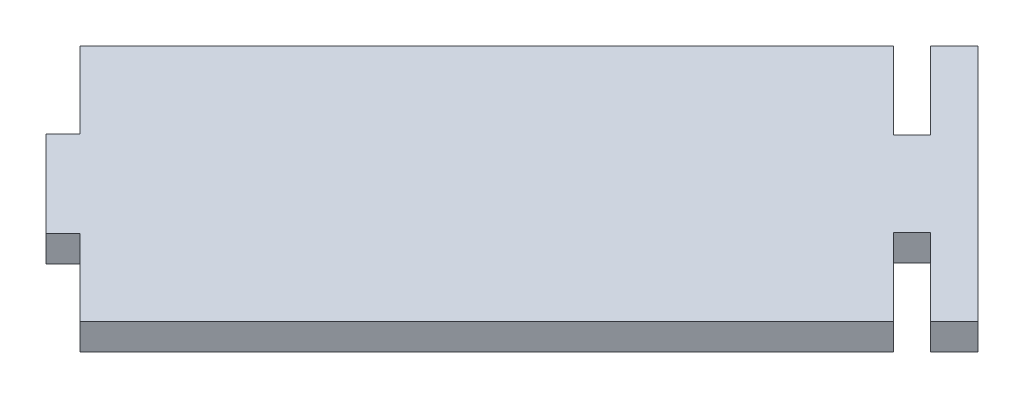
SolidWorks part; units mm, degrees
material "cardboard"
ref_plane "Front Plane" through (0, 0, 0) normal (0, 0, 1) x (1, 0, 0)
ref_plane "Top Plane" through (0, 0, 0) normal (0, 1, 0) x (1, 0, 0)
ref_plane "Right Plane" through (0, 0, 0) normal (1, 0, 0) x (0, 0, -1)
sketch "Sketch1" plane through (0, 0, 0) normal (0, 1, 0) x (1, 0, 0)
  line L0 (-130.0272, 126.0966) -> (-119.0272, 126.0966)
  line L1 (-120.0272, 122.0966) -> (-120.0272, 106.0966)
  line L2 (-60.2272, 122.0966) -> (-60.2272, 106.0966)
  line L3 (-117.6272, 106.0966) -> (-120.0272, 106.0966)
  line L4 (-131.4272, 122.0966) -> (-129.0272, 122.0966)
  line L5 (-131.4272, 122.0966) -> (-131.4272, 106.0966)
  line L6 (-131.4272, 106.0966) -> (-129.0272, 106.0966)
  line L7 (-129.0272, 122.0966) -> (-129.0272, 106.0966)
  line L8 (-117.6272, 122.0966) -> (-117.6272, 106.0966)
  line L9 (-117.6272, 122.0966) -> (-120.0272, 122.0966)
  line L10 (-57.8272, 122.0966) -> (-57.8272, 106.0966)
  line L11 (-94.4272, 126.0966) -> (-83.4272, 126.0966)
  line L12 (-60.2272, 122.0966) -> (-57.8272, 122.0966)
  line L13 (-60.2272, 106.0966) -> (-57.8272, 106.0966)
  line L14 (-48.8272, 122.0966) -> (-48.8272, 106.0966)
  line L15 (-46.4272, 122.0966) -> (-48.8272, 122.0966)
  line L16 (-46.4272, 122.0966) -> (-46.4272, 106.0966)
  line L17 (-46.4272, 106.0966) -> (-48.8272, 106.0966)
  line L18 (10.9728, 122.0966) -> (10.9728, 106.0966)
  line L19 (13.3728, 122.0966) -> (13.3728, 106.0966)
  line L20 (10.9728, 122.0966) -> (13.3728, 122.0966)
  line L21 (10.9728, 106.0966) -> (13.3728, 106.0966)
  line L22 (22.3728, 122.0966) -> (22.3728, 106.0966)
  line L23 (24.7728, 122.0966) -> (22.3728, 122.0966)
  line L24 (24.7728, 122.0966) -> (24.7728, 106.0966)
  line L25 (24.7728, 106.0966) -> (22.3728, 106.0966)
  line L26 (82.1728, 122.0966) -> (82.1728, 106.0966)
  line L27 (84.5728, 122.0966) -> (84.5728, 106.0966)
  line L28 (-58.8272, 126.0966) -> (-47.8272, 126.0966)
  line L29 (82.1728, 122.0966) -> (84.5728, 122.0966)
  line L30 (82.1728, 106.0966) -> (84.5728, 106.0966)
  line L31 (93.5728, 122.0966) -> (93.5728, 106.0966)
  line L32 (58.9728, 128.0966) -> (83.5728, 128.0966)
  line L33 (95.9728, 122.0966) -> (93.5728, 122.0966)
  line L34 (95.9728, 122.0966) -> (95.9728, 106.0966)
  line L35 (95.9728, 106.0966) -> (93.5728, 106.0966)
  line L36 (65.0298, 36.0601) -> (71.4457, 29.6442)
  line L37 (84.9326, 16.1573) -> (86.9125, 18.1372)
  line L38 (65.0298, 36.0601) -> (67.0097, 38.04)
  line L39 (78.5168, 22.5731) -> (84.9326, 16.1573)
  line L40 (84.9326, -86.6937) -> (78.5168, -93.1095)
  line L41 (84.9326, -86.6937) -> (86.9125, -88.6736)
  line L42 (86.9125, -88.6736) -> (67.0097, -108.5764)
  line L43 (65.0298, -106.5965) -> (67.0097, -108.5764)
  line L44 (71.4457, -100.1806) -> (65.0298, -106.5965)
  line L45 (-37.8211, -106.5965) -> (-44.237, -100.1806)
  line L46 (-37.8211, -106.5965) -> (-39.801, -108.5764)
  line L47 (-39.801, -108.5764) -> (-59.7038, -88.6736)
  line L48 (-57.7239, -86.6937) -> (-59.7038, -88.6736)
  line L49 (-51.308, -93.1095) -> (-57.7239, -86.6937)
  line L50 (-23.2272, 126.0966) -> (-12.2272, 126.0966)
  line L51 (12.3728, 126.0966) -> (23.3728, 126.0966)
  line L52 (47.9728, 126.0966) -> (58.9728, 126.0966)
  line L53 (83.5728, 126.0966) -> (94.5728, 126.0966)
  line L54 (119.1728, 126.0966) -> (130.1728, 126.0966)
  line L55 (-34.4977, -103.2731) -> (-32.4283, -105.3425)
  line L56 (-4.0921, -77.1101) -> (-2.0227, -79.1795)
  line L57 (-54.4005, -83.3703) -> (-56.1683, -85.138)
  line L58 (-34.4977, -103.2731) -> (-36.2655, -105.0408)
  line L59 (-30.307, -50.8953) -> (-56.4699, -77.0582)
  line L60 (-56.4699, -81.3008) -> (-54.4005, -83.3703)
  line L61 (-2.0227, -79.1795) -> (-28.1856, -105.3425)
  line L62 (-30.307, -50.8953) -> (-28.2375, -52.9647)
  line L63 (-142.3272, 128.0966) -> (-130.0272, 128.0966)
  line L64 (-53.7115, 80.7984) -> (-53.7115, 85.7984)
  line L65 (-63.7115, 80.7984) -> (-63.7115, 85.7984)
  line L66 (-33.1616, 72.2863) -> (-29.6261, 75.8218)
  line L67 (-26.0906, 65.2152) -> (-22.555, 68.7508)
  line L68 (-17.5785, 44.6653) -> (-12.5785, 44.6653)
  line L69 (-17.5785, 34.6653) -> (-12.5785, 34.6653)
  line L70 (-26.0906, 14.1154) -> (-22.555, 10.5799)
  line L71 (-33.1616, 7.0443) -> (-29.6261, 3.5088)
  line L72 (-53.7115, -1.4677) -> (-53.7115, -6.4677)
  line L73 (-63.7115, -1.4677) -> (-63.7115, -6.4677)
  line L74 (-84.2615, 7.0443) -> (-87.797, 3.5088)
  line L75 (63.4742, 34.5044) -> (69.8901, 28.0886)
  line L76 (76.9611, 21.0175) -> (83.377, 14.6016)
  line L77 (76.9611, 21.0175) -> (78.5168, 22.5731)
  line L78 (69.8901, 28.0886) -> (71.4457, 29.6442)
  line L79 (31.6778, -78.9012) -> (34.5062, -76.0728)
  line L80 (57.2374, -17.1948) -> (54.409, -14.3664)
  line L81 (-142.3272, 128.0966) -> (-142.3272, 118.0966)
  line L82 (-4.469, 8.3648) -> (-30.0287, -17.1948)
  line L83 (-142.3272, 100.0966) -> (-126.5272, 100.0966)
  line L84 (-91.3325, 14.1154) -> (-94.8681, 10.5799)
  line L85 (-106.7272, 119.0966) -> (-106.7272, 109.0966)
  line L86 (67.0097, 38.04) -> (86.9125, 18.1372)
  line L87 (-20.8129, -49.7827) -> (-0.9101, -69.6855)
  line L88 (-20.8129, -49.7827) -> (-23.9949, -52.9647)
  line L89 (-0.9101, -69.6855) -> (-4.0921, -72.8675)
  line L90 (-30.0287, -17.1948) -> (-65.0287, -17.1948)
  line L91 (-80.0287, -32.1948) -> (-80.0287, -38.3416)
  line L92 (-65.0287, -53.3416) -> (-32.7533, -53.3416)
  line L93 (-110.0272, 105.0966) -> (-112.5272, 105.0966)
  line L94 (-139.0272, 125.0966) -> (-136.5272, 125.0966)
  line L95 (-139.0272, 125.0966) -> (-139.0272, 105.0966)
  line L96 (-139.0272, 105.0966) -> (-136.5272, 105.0966)
  line L97 (-136.5272, 125.0966) -> (-136.5272, 105.0966)
  line L98 (-112.5272, 125.0966) -> (-112.5272, 105.0966)
  line L99 (31.6778, 8.3648) -> (31.6778, 43.3648)
  line L100 (16.6778, 58.3648) -> (10.531, 58.3648)
  line L101 (-4.469, 43.3648) -> (-4.469, 8.3648)
  line L102 (-110.0272, 125.0966) -> (-112.5272, 125.0966)
  line L103 (-110.0272, 125.0966) -> (-110.0272, 105.0966)
  line L104 (-122.5272, 100.0966) -> (-108.2272, 100.0966)
  line L105 (-106.7272, 119.0966) -> (-106.7272, 109.0966)
  line L106 (57.2374, -53.3416) -> (92.2374, -53.3416)
  line L107 (107.2374, -38.3416) -> (107.2374, -32.1948)
  line L108 (92.2374, -17.1948) -> (57.2374, -17.1948)
  line L109 (-72.6272, 100.0966) -> (-71.1272, 100.0966)
  line L110 (-71.1272, 128.0966) -> (-71.1272, 100.0966)
  line L111 (23.3728, 128.0966) -> (47.9728, 128.0966)
  line L112 (-71.1272, 128.0966) -> (-71.1272, 100.0966)
  line L113 (-71.1272, 100.0966) -> (-35.5272, 100.0966)
  line L114 (-35.5272, 128.0966) -> (-35.5272, 100.0966)
  line L115 (-4.469, -81.6259) -> (-4.469, -113.9012)
  line L116 (10.531, -128.9012) -> (16.6778, -128.9012)
  line L117 (31.6778, -113.9012) -> (31.6778, -78.9012)
  line L118 (-12.2272, 128.0966) -> (12.3728, 128.0966)
  line L119 (-35.5272, 128.0966) -> (-35.5272, 100.0966)
  line L120 (-35.5272, 100.0966) -> (0.0728, 100.0966)
  line L121 (0.0728, 128.0966) -> (0.0728, 100.0966)
  line L122 (-47.8272, 128.0966) -> (-23.2272, 128.0966)
  line L123 (0.0728, 128.0966) -> (0.0728, 100.0966)
  line L124 (54.409, -56.17) -> (57.2374, -53.3416)
  line L125 (28.1189, -69.6855) -> (48.0217, -49.7827)
  line L126 (83.377, -85.138) -> (76.9611, -91.5539)
  line L127 (48.0217, -49.7827) -> (83.377, -85.138)
  line L128 (76.9611, -91.5539) -> (78.5168, -93.1095)
  line L129 (80.4967, -95.0894) -> (73.4256, -102.1605)
  line L130 (28.1189, -69.6855) -> (63.4742, -105.0408)
  line L131 (69.8901, -98.625) -> (71.4457, -100.1806)
  line L132 (69.8901, -98.625) -> (63.4742, -105.0408)
  line L133 (-36.2655, -105.0408) -> (-42.6813, -98.625)
  line L134 (-42.6813, -98.625) -> (-44.237, -100.1806)
  line L135 (34.5062, 5.5364) -> (31.6778, 8.3648)
  line L136 (-99.8446, 34.6653) -> (-104.8446, 34.6653)
  line L137 (48.0217, -20.7537) -> (28.1189, -0.8509)
  line L138 (48.0217, -20.7537) -> (83.377, 14.6016)
  line L139 (28.1189, -0.8509) -> (63.4742, 34.5044)
  line L140 (-46.2169, -102.1605) -> (-53.2879, -95.0894)
  line L141 (-49.7524, -91.5539) -> (-51.308, -93.1095)
  line L142 (-49.7524, -91.5539) -> (-56.1683, -85.138)
  line L143 (-63.7115, 80.7984) -> (-75.7494, 80.7984)
  line L144 (-75.7494, 80.7984) -> (-84.2615, 72.2863)
  line L145 (0.0728, 100.0966) -> (35.6728, 100.0966)
  line L146 (35.6728, 128.0966) -> (35.6728, 100.0966)
  line L147 (-83.4272, 128.0966) -> (-58.8272, 128.0966)
  line L148 (35.6728, 128.0966) -> (35.6728, 100.0966)
  line L149 (35.6728, 100.0966) -> (71.2728, 100.0966)
  line L150 (71.2728, 128.0966) -> (71.2728, 100.0966)
  line L151 (-119.0272, 128.0966) -> (-108.2272, 128.0966)
  line L152 (71.2728, 128.0966) -> (71.2728, 100.0966)
  line L153 (71.2728, 100.0966) -> (106.8728, 100.0966)
  line L154 (106.8728, 128.0966) -> (106.8728, 100.0966)
  line L155 (130.1728, 128.0966) -> (142.4728, 128.0966)
  line L156 (106.8728, 128.0966) -> (106.8728, 100.0966)
  line L157 (106.8728, 100.0966) -> (142.4728, 100.0966)
  line L158 (142.4728, 128.0966) -> (142.4728, 118.0966)
  line L159 (-67.8272, 125.0966) -> (-65.3272, 125.0966)
  line L160 (-67.8272, 125.0966) -> (-67.8272, 105.0966)
  line L161 (-67.8272, 105.0966) -> (-65.3272, 105.0966)
  line L162 (-65.3272, 125.0966) -> (-65.3272, 105.0966)
  line L163 (-41.3272, 125.0966) -> (-41.3272, 105.0966)
  line L164 (-38.8272, 105.0966) -> (-41.3272, 105.0966)
  line L165 (-38.8272, 125.0966) -> (-38.8272, 105.0966)
  line L166 (-38.8272, 125.0966) -> (-41.3272, 125.0966)
  line L167 (-59.3272, 100.0966) -> (-59.3272, 96.0966)
  line L168 (-59.3272, 96.0966) -> (-47.3272, 96.0966)
  line L169 (-47.3272, 96.0966) -> (-47.3272, 100.0966)
  line L170 (3.3728, 125.0966) -> (5.8728, 125.0966)
  line L171 (3.3728, 125.0966) -> (3.3728, 105.0966)
  line L172 (3.3728, 105.0966) -> (5.8728, 105.0966)
  line L173 (5.8728, 125.0966) -> (5.8728, 105.0966)
  line L174 (29.8728, 125.0966) -> (29.8728, 105.0966)
  line L175 (32.3728, 105.0966) -> (29.8728, 105.0966)
  line L176 (32.3728, 125.0966) -> (32.3728, 105.0966)
  line L177 (32.3728, 125.0966) -> (29.8728, 125.0966)
  line L178 (11.8728, 100.0966) -> (11.8728, 96.0966)
  line L179 (11.8728, 96.0966) -> (23.8728, 96.0966)
  line L180 (23.8728, 96.0966) -> (23.8728, 100.0966)
  line L181 (74.5728, 125.0966) -> (77.0728, 125.0966)
  line L182 (74.5728, 125.0966) -> (74.5728, 105.0966)
  line L183 (74.5728, 105.0966) -> (77.0728, 105.0966)
  line L184 (77.0728, 125.0966) -> (77.0728, 105.0966)
  line L185 (101.0728, 125.0966) -> (101.0728, 105.0966)
  line L186 (103.5728, 105.0966) -> (101.0728, 105.0966)
  line L187 (103.5728, 125.0966) -> (103.5728, 105.0966)
  line L188 (103.5728, 125.0966) -> (101.0728, 125.0966)
  line L189 (83.0728, 100.0966) -> (83.0728, 96.0966)
  line L190 (83.0728, 96.0966) -> (95.0728, 96.0966)
  line L191 (95.0728, 96.0966) -> (95.0728, 100.0966)
  line L192 (-126.5272, 100.0966) -> (-126.5272, 101.0966)
  line L193 (-126.5272, 101.0966) -> (-122.5272, 101.0966)
  line L194 (-122.5272, 101.0966) -> (-122.5272, 100.0966)
  line L195 (-59.3272, 99.0966) -> (-55.3272, 99.0966)
  line L196 (-55.3272, 99.0966) -> (-55.3272, 101.0966)
  line L197 (-55.3272, 101.0966) -> (-51.3272, 101.0966)
  line L198 (-51.3272, 101.0966) -> (-51.3272, 99.0966)
  line L199 (-51.3272, 99.0966) -> (-47.3272, 99.0966)
  line L200 (11.8728, 99.0966) -> (15.8728, 99.0966)
  line L201 (15.8728, 99.0966) -> (15.8728, 101.0966)
  line L202 (15.8728, 101.0966) -> (19.8728, 101.0966)
  line L203 (29.5331, 0.5633) -> (35.897, -5.8007)
  line L204 (35.897, -5.8007) -> (33.0686, -8.6291)
  line L205 (33.0686, -8.6291) -> (40.2435, -15.8039)
  line L206 (40.2435, -15.8039) -> (43.0719, -12.9755)
  line L207 (43.0719, -12.9755) -> (49.4359, -19.3395)
  line L208 (49.4359, -51.1969) -> (43.0719, -57.5609)
  line L209 (43.0719, -57.5609) -> (40.2435, -54.7324)
  line L210 (40.2435, -54.7324) -> (33.0686, -61.9073)
  line L211 (33.0686, -61.9073) -> (35.897, -64.7357)
  line L212 (35.897, -64.7357) -> (29.5331, -71.0997)
  line L213 (-2.3243, -71.0997) -> (-8.6883, -64.7357)
  line L214 (-8.6883, -64.7357) -> (-5.8599, -61.9073)
  line L215 (-5.8599, -61.9073) -> (-13.0347, -54.7324)
  line L216 (-13.0347, -54.7324) -> (-15.8632, -57.5609)
  line L217 (-15.8632, -57.5609) -> (-22.2271, -51.1969)
  line L218 (-87.797, 75.8218) -> (-94.8681, 68.7508)
  line L219 (-91.3325, 65.2152) -> (-99.8446, 56.7032)
  line L220 (-99.8446, 56.7032) -> (-99.8446, 44.6653)
  line L221 (-104.8446, 44.6653) -> (-104.8446, 34.6653)
  line L222 (-99.8446, 34.6653) -> (-99.8446, 22.6275)
  line L223 (-99.8446, 22.6275) -> (-91.3325, 14.1154)
  line L224 (-94.8681, 10.5799) -> (-87.797, 3.5088)
  line L225 (-84.2615, 7.0443) -> (-75.7494, -1.4677)
  line L226 (-75.7494, -1.4677) -> (-63.7115, -1.4677)
  line L227 (-63.7115, -6.4677) -> (-53.7115, -6.4677)
  line L228 (-53.7115, -1.4677) -> (-41.6737, -1.4677)
  line L229 (-41.6737, -1.4677) -> (-33.1616, 7.0443)
  line L230 (-29.6261, 3.5088) -> (-22.555, 10.5799)
  line L231 (-26.0906, 14.1154) -> (-17.5785, 22.6275)
  line L232 (-17.5785, 22.6275) -> (-17.5785, 34.6653)
  line L233 (-12.5785, 34.6653) -> (-12.5785, 44.6653)
  line L234 (-17.5785, 44.6653) -> (-17.5785, 56.7032)
  line L235 (-17.5785, 56.7032) -> (-26.0906, 65.2152)
  line L236 (-22.555, 68.7508) -> (-29.6261, 75.8218)
  line L237 (-33.1616, 72.2863) -> (-41.6737, 80.7984)
  line L238 (-41.6737, 80.7984) -> (-53.7115, 80.7984)
  line L239 (-53.7115, 85.7984) -> (-63.7115, 85.7984)
  line L240 (-99.8446, 44.6653) -> (-104.8446, 44.6653)
  line L241 (-91.3325, 65.2152) -> (-94.8681, 68.7508)
  line L242 (-84.2615, 72.2863) -> (-87.797, 75.8218)
  line L243 (19.8728, 101.0966) -> (19.8728, 99.0966)
  line L244 (19.8728, 99.0966) -> (23.8728, 99.0966)
  line L245 (83.0728, 99.0966) -> (87.0728, 99.0966)
  line L246 (87.0728, 99.0966) -> (87.0728, 101.0966)
  line L247 (87.0728, 101.0966) -> (91.0728, 101.0966)
  line L248 (91.0728, 101.0966) -> (91.0728, 99.0966)
  line L249 (91.0728, 99.0966) -> (95.0728, 99.0966)
  line L250 (142.4728, 118.0966) -> (144.4728, 118.0966)
  line L251 (144.4728, 110.0966) -> (142.4728, 110.0966)
  line L252 (142.4728, 110.0966) -> (142.4728, 100.0966)
  line L253 (-142.3272, 118.0966) -> (-141.3272, 118.0966)
  line L254 (-141.3272, 118.0966) -> (-141.3272, 110.0966)
  line L255 (-141.3272, 110.0966) -> (-142.3272, 110.0966)
  line L256 (-142.3272, 110.0966) -> (-142.3272, 100.0966)
  line L257 (-108.2272, 128.0966) -> (-108.2272, 119.0966)
  line L258 (-108.2272, 119.0966) -> (-106.7272, 119.0966)
  line L259 (-106.7272, 109.0966) -> (-108.2272, 109.0966)
  line L260 (-108.2272, 109.0966) -> (-108.2272, 100.0966)
  line L261 (-72.6272, 128.0966) -> (-72.6272, 119.0966)
  line L262 (-72.6272, 119.0966) -> (-69.6272, 119.0966)
  line L263 (-69.6272, 119.0966) -> (-69.6272, 109.0966)
  line L264 (-69.6272, 109.0966) -> (-72.6272, 109.0966)
  line L265 (-72.6272, 109.0966) -> (-72.6272, 100.0966)
  line L266 (-37.0272, 128.0966) -> (-37.0272, 119.0966)
  line L267 (-37.0272, 119.0966) -> (-34.0272, 119.0966)
  line L268 (-34.0272, 119.0966) -> (-34.0272, 109.0966)
  line L269 (-34.0272, 109.0966) -> (-37.0272, 109.0966)
  line L270 (-37.0272, 109.0966) -> (-37.0272, 100.0966)
  line L271 (-1.4272, 128.0966) -> (-1.4272, 119.0966)
  line L272 (-1.4272, 119.0966) -> (1.5728, 119.0966)
  line L273 (1.5728, 119.0966) -> (1.5728, 109.0966)
  line L274 (1.5728, 109.0966) -> (-1.4272, 109.0966)
  line L275 (-1.4272, 109.0966) -> (-1.4272, 100.0966)
  line L276 (34.1728, 128.0966) -> (34.1728, 119.0966)
  line L277 (34.1728, 119.0966) -> (37.1728, 119.0966)
  line L278 (37.1728, 119.0966) -> (37.1728, 109.0966)
  line L279 (37.1728, 109.0966) -> (34.1728, 109.0966)
  line L280 (34.1728, 109.0966) -> (34.1728, 100.0966)
  line L281 (69.7728, 128.0966) -> (69.7728, 119.0966)
  line L282 (69.7728, 119.0966) -> (72.7728, 119.0966)
  line L283 (72.7728, 119.0966) -> (72.7728, 109.0966)
  line L284 (72.7728, 109.0966) -> (69.7728, 109.0966)
  line L285 (69.7728, 109.0966) -> (69.7728, 100.0966)
  line L286 (105.3728, 128.0966) -> (105.3728, 119.0966)
  line L287 (105.3728, 119.0966) -> (108.3728, 119.0966)
  line L288 (108.3728, 119.0966) -> (108.3728, 109.0966)
  line L289 (108.3728, 109.0966) -> (105.3728, 109.0966)
  line L290 (105.3728, 109.0966) -> (105.3728, 100.0966)
  line L291 (144.4728, 118.0966) -> (144.4728, 110.0966)
  line L292 (-130.0272, 128.0966) -> (-130.0272, 126.0966)
  line L293 (-119.0272, 128.0966) -> (-119.0272, 126.0966)
  line L294 (-94.4272, 128.0966) -> (-94.4272, 126.0966)
  line L295 (-83.4272, 128.0966) -> (-83.4272, 126.0966)
  line L296 (-58.8272, 128.0966) -> (-58.8272, 126.0966)
  line L297 (-47.8272, 128.0966) -> (-47.8272, 126.0966)
  line L298 (-23.2272, 128.0966) -> (-23.2272, 126.0966)
  line L299 (-12.2272, 128.0966) -> (-12.2272, 126.0966)
  line L300 (12.3728, 128.0966) -> (12.3728, 126.0966)
  line L301 (23.3728, 128.0966) -> (23.3728, 126.0966)
  line L302 (47.9728, 128.0966) -> (47.9728, 126.0966)
  line L303 (58.9728, 128.0966) -> (58.9728, 126.0966)
  line L304 (83.5728, 128.0966) -> (83.5728, 126.0966)
  line L305 (94.5728, 128.0966) -> (94.5728, 126.0966)
  line L306 (119.1728, 128.0966) -> (119.1728, 126.0966)
  line L307 (130.1728, 128.0966) -> (130.1728, 126.0966)
  line L308 (94.5728, 128.0966) -> (119.1728, 128.0966)
  circle A0 centre (-30.307, -57.9663) radius 1.75
  circle A1 centre (-58.7115, 66.6653) radius 6
  circle A2 centre (-39.6197, 58.7572) radius 6
  circle A3 centre (-31.7115, 39.6653) radius 6
  circle A4 centre (-9.0938, -79.1795) radius 1.75
  circle A5 centre (-30.307, -100.3927) radius 1.75
  circle A6 centre (13.6044, 33.3648) radius 10
  circle A7 centre (-124.5272, 112.5966) radius 1
  circle A8 centre (-51.5202, -79.1795) radius 1.75
  arc A9 (-28.2375, -52.9647) -> (-23.9949, -52.9647) centre (-26.1162, -50.8434) ccw
  arc A10 (-4.0921, -77.1101) -> (-4.0921, -72.8675) centre (-1.9708, -74.9888) cw
  circle A11 centre (-53.3272, 112.5966) radius 1
  circle A12 centre (82.2374, -35.2682) radius 10
  circle A13 centre (13.6044, -35.2682) radius 15
  arc A14 (-65.0287, -17.1948) -> (-80.0287, -32.1948) centre (-65.0287, -32.1948) ccw
  arc A15 (-80.0287, -38.3416) -> (-65.0287, -53.3416) centre (-65.0287, -38.3416) ccw
  arc A16 (-4.469, -113.9012) -> (10.531, -128.9012) centre (10.531, -113.9012) ccw
  arc A17 (16.6778, -128.9012) -> (31.6778, -113.9012) centre (16.6778, -113.9012) ccw
  arc A18 (92.2374, -53.3416) -> (107.2374, -38.3416) centre (92.2374, -38.3416) ccw
  arc A19 (107.2374, -32.1948) -> (92.2374, -17.1948) centre (92.2374, -32.1948) ccw
  arc A20 (31.6778, 43.3648) -> (16.6778, 58.3648) centre (16.6778, 43.3648) ccw
  circle A21 centre (17.8728, 112.5966) radius 1
  circle A22 centre (13.6044, -103.9012) radius 10
  circle A23 centre (89.0728, 112.5966) radius 1
  circle A24 centre (-55.0287, -35.2682) radius 10
  circle A25 centre (-39.6197, 20.5734) radius 6
  circle A26 centre (-88.9272, 114.0966) radius 7.5
  circle A27 centre (-17.7272, 114.0966) radius 7.5
  circle A28 centre (53.4728, 114.0966) radius 7.5
  circle A29 centre (124.6728, 114.0966) radius 7.5
  arc A30 (10.531, 58.3648) -> (-4.469, 43.3648) centre (10.531, 43.3648) ccw
  arc A31 (-32.4283, -105.3425) -> (-28.1856, -105.3425) centre (-30.307, -103.2212) ccw
  arc A32 (-56.4699, -77.0582) -> (-56.4699, -81.3008) centre (-54.3486, -79.1795) ccw
  circle A33 centre (-58.7115, 12.6653) radius 6
  circle A34 centre (-77.8034, 20.5734) radius 6
  circle A35 centre (-85.7115, 39.6653) radius 6
  circle A36 centre (-77.8034, 58.7572) radius 6
  circle A37 centre (-58.7115, 39.6653) radius 15
  point P67 (13.6044, -35.2682)
  point P113 (13.6044, -35.2682)
  point P166 (13.6044, -35.2682)
  point P168 (13.6044, -35.2682)
  point P177 (13.6044, -35.2682)
  point P182 (13.6044, -35.2682)
  point P246 (13.6044, -35.2682)
  point P268 (13.6044, -35.2682)
  point P279 (13.6044, -35.2682)
  point P313 (-58.7115, 39.6653)
  point P314 (-58.7115, 39.6653)
  point P399 (-58.7115, 39.6653)
extrude "Boss-Extrude1" add sketch "Sketch1" along normal blind 2.2 contours L206 L207 L138 L76 L77 L39 L37 L86 L38 L36 L78 L75 L139 L203 L204 L137
